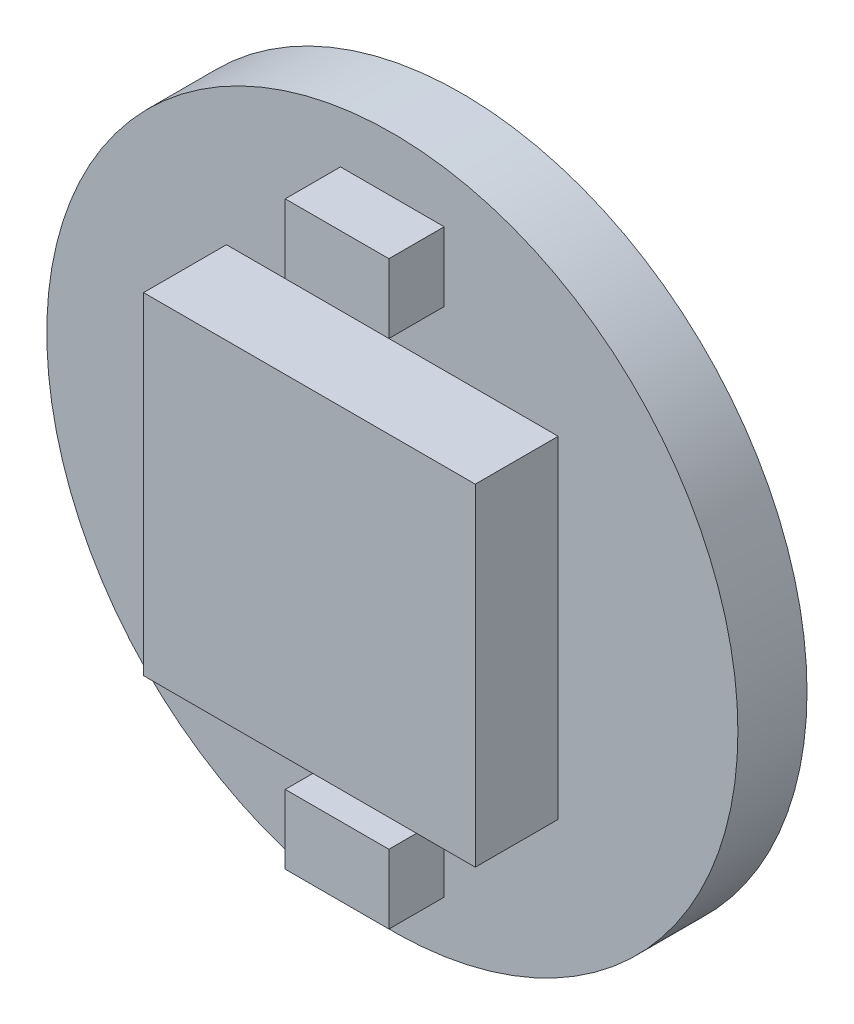
SolidWorks part; units mm, degrees
ref_plane "Front Plane" through (0, 0, 0) normal (0, 0, 1) x (1, 0, 0)
ref_plane "Top Plane" through (0, 0, 0) normal (0, 1, 0) x (1, 0, 0)
ref_plane "Right Plane" through (0, 0, 0) normal (1, 0, 0) x (0, 0, -1)
sketch "Sketch1" plane through (0, 0, 0) normal (0, 0, 1) x (1, 0, 0)
  circle A0 centre (0, 0) radius 5
  dimension "D1" = 10
extrude "Boss-Extrude1" add sketch "Sketch1" along normal blind 1
sketch "Sketch2" plane through (0, 0, 1) normal (0, 0, 1) x (1, 0, 0)
  line L1 (-2.4, 2.4) -> (2.4, 2.4)
  line L2 (-2.4, 2.4) -> (-2.4, -2.4)
  line L3 (-2.4, -2.4) -> (2.4, -2.4)
  line L4 (2.4, 2.4) -> (2.4, -2.4)
  line L5 (-2.4, 2.4) -> (2.4, -2.4) construction
  line L6 (-2.4, -2.4) -> (2.4, 2.4) construction
  point P0 (0, 0)
  dimension "D1" = 4.8
  dimension "D2" = 4.8
extrude "Boss-Extrude2" add sketch "Sketch2" along normal blind 1.2
sketch "Sketch3" plane through (0, 0, 1) normal (0, 0, 1) x (1, 0, 0)
  line L0 (0, 5) -> (0, -5) construction
  line L1 (0, 5) -> (0, 2.4)
  line L2 (2.4, 2.4) -> (-2.4, 2.4) construction
  line L3 (-5, 0) -> (5, 0) construction
  line L4 (-0.75, 4.2) -> (0.75, 4.2)
  line L5 (-0.75, 4.2) -> (-0.75, 3.2)
  line L6 (-0.75, 3.2) -> (0.75, 3.2)
  line L7 (0.75, 4.2) -> (0.75, 3.2)
  line L8 (-0.75, 4.2) -> (0.75, 3.2) construction
  line L9 (-0.75, 3.2) -> (0.75, 4.2) construction
  line L10 (-0.75, -3.2) -> (0.75, -3.2)
  line L11 (0.75, -4.2) -> (0.75, -3.2)
  line L12 (-0.75, -4.2) -> (0.75, -4.2)
  line L13 (-0.75, -4.2) -> (-0.75, -3.2)
  circle A0 centre (0, 0) radius 5 construction
  point P5 (0, 3.7)
  dimension "D1" = 1
  dimension "D2" = 1.5
extrude "Boss-Extrude3" add sketch "Sketch3" along normal blind 0.8 contours L13 L12 L11 L10 | L7 L4 L1 L6 | L5 L6 L1 L4
